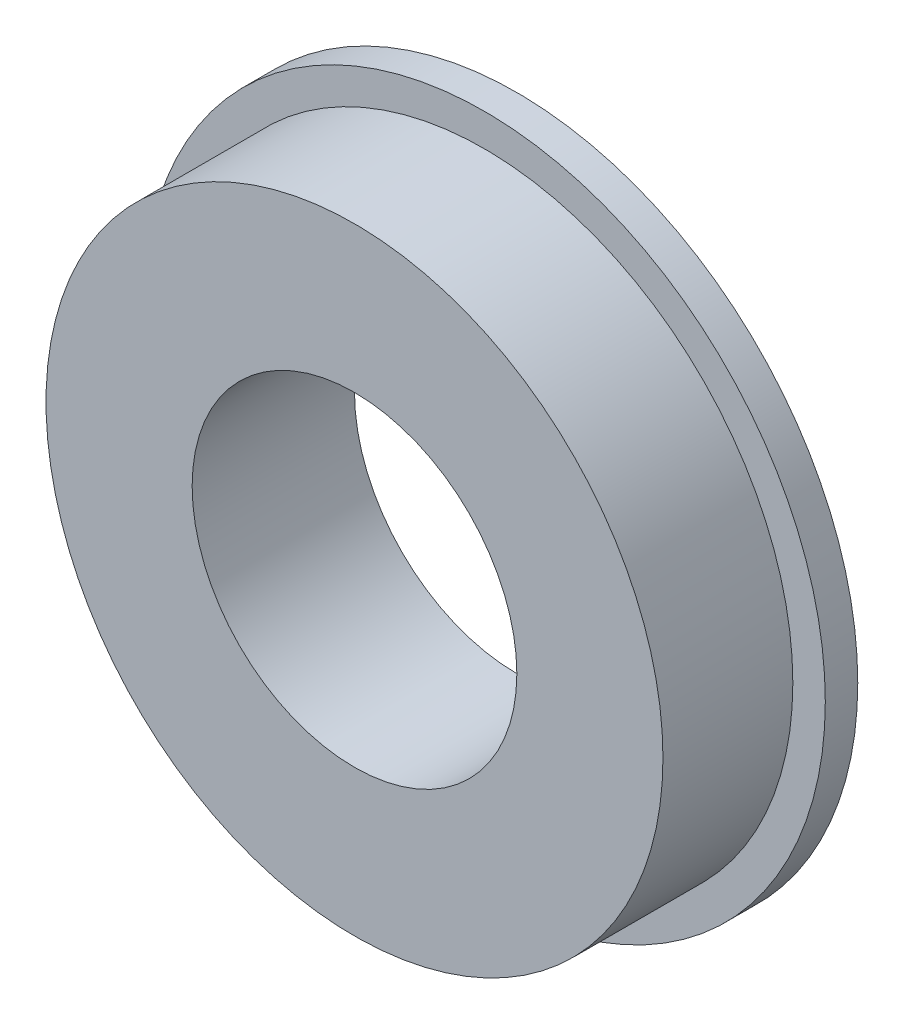
SolidWorks part; units mm, degrees
ref_plane "前视基准面" through (0, 0, 0) normal (0, 0, 1) x (1, 0, 0)
ref_plane "上视基准面" through (0, 0, 0) normal (0, 1, 0) x (1, 0, 0)
ref_plane "右视基准面" through (0, 0, 0) normal (1, 0, 0) x (0, 0, -1)
sketch "草图1" plane through (0, 0, 0) normal (0, 0, 1) x (1, 0, 0)
  circle A0 centre (0, 0) radius 10.5
extrude "凸台-拉伸1" add sketch "草图1" along normal blind 1
sketch "草图2" plane through (0, 0, 1) normal (0, 0, 1) x (1, 0, 0)
  circle A0 centre (0, 0) radius 9.5
extrude "凸台-拉伸2" add sketch "草图2" along normal blind 4
sketch "草图3" plane through (0, 0, 5) normal (0, 0, 1) x (1, 0, 0)
  circle A0 centre (0, 0) radius 5
extrude "切除-拉伸1" cut sketch "草图3" against normal blind 5
